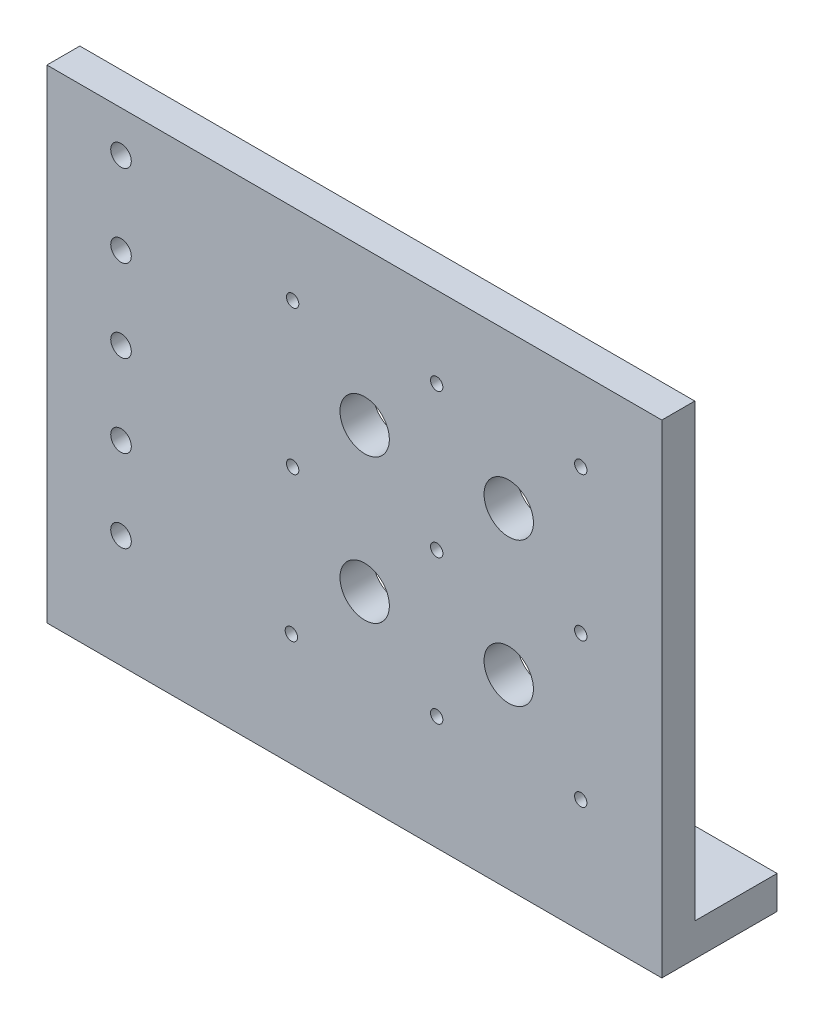
SolidWorks part; units mm, degrees
ref_plane "Front Plane" through (0, 0, 0) normal (0, 0, 1) x (1, 0, 0)
ref_plane "Top Plane" through (0, 0, 0) normal (0, 1, 0) x (1, 0, 0)
ref_plane "Right Plane" through (0, 0, 0) normal (1, 0, 0) x (0, 0, -1)
sketch "Sketch1" plane through (0, 0, 0) normal (0, 0, 1) x (1, 0, 0)
  line L0 (-72.2, 72.2) -> (37.2, 72.2)
  line L5 (-57.2, 57.2) -> (22.2, 57.2)
  line L6 (-57.2, 57.2) -> (-57.2, -22.2)
  line L7 (-57.2, -22.2) -> (22.2, -22.2)
  line L8 (22.2, 57.2) -> (22.2, -22.2)
  line L9 (37.2, 72.2) -> (37.2, -37.2)
  line L10 (-72.2, -37.2) -> (37.2, -37.2)
  line L11 (-72.2, 72.2) -> (-72.2, -37.2)
  circle A0 centre (-52.5, 52.5) radius 1.5
  circle A1 centre (-17.5, 52.5) radius 1.5
  circle A2 centre (17.5, 52.5) radius 1.5
  circle A3 centre (-52.5, 17.5) radius 1.5
  circle A4 centre (-17.5, 17.5) radius 1.5
  circle A5 centre (17.5, 17.5) radius 1.5
  circle A6 centre (17.5, -17.5) radius 1.5
  circle A7 centre (-17.5, -17.5) radius 1.5
  circle A8 centre (-52.8099, -17.8099) radius 1.5
  circle A9 centre (-35, 35) radius 6
  circle A10 centre (0, 35) radius 6
  circle A11 centre (0, 0) radius 6
  circle A12 centre (-35, 0) radius 6
  point P49 (-17.5, 17.5)
  dimension "D1" = 15
  dimension "D2" = 4
extrude "Boss-Extrude1" add sketch "Sketch1" along normal blind 8 contours L8 L5 L6 L7 A12 A11 A10 A9 A8 A7 A6 A5 A4 A3 A2 A1 A0 | L0 L11 L10 L9 L5 L8 L7 L6
sketch "Sketch2" plane through (0, 72.2, 0) normal (0, 1, 0) x (1, 0, 0)
  line L1 (-72.2, -8) -> (-112.2, -8)
  line L2 (-72.2, -8) -> (-72.2, 0)
  line L3 (-72.2, 0) -> (-112.2, 0)
  line L4 (-112.2, -8) -> (-112.2, 0)
  dimension "D1" = 40
extrude "Boss-Extrude2" add sketch "Sketch2" against normal up to surface (109.4 mm away) contours L2 L1 L4 L3 up to face at (-17.5, -37.2, 4)
sketch "Sketch4" plane through (0, 0, 0) normal (0, 0, -1) x (-1, 0, 0)
  line L0 (112.2, 72.2) -> (-37.2, 72.2) construction
  line L1 (112.2, -37.2) -> (112.2, 72.2) construction
  circle A0 centre (94.2, 62.2) radius 2.5
  circle A1 centre (94.2, 42.2) radius 2.5
  circle A2 centre (94.2, 22.2) radius 2.5
  circle A3 centre (94.2, 2.2) radius 2.5
  circle A4 centre (94.2, -17.8) radius 2.5
  dimension "D1" = 5
  dimension "D2" = 10
  dimension "D3" = 18
  dimension "D4" = 5
extrude "Cut-Extrude1" cut sketch "Sketch4" against normal blind 25
sketch "Sketch5" plane through (0, -37.2, 0) normal (0, -1, 0) x (1, 0, 0)
  line L1 (-112.2, 0) -> (37.2, 0)
  line L2 (-112.2, 0) -> (-112.2, -20)
  line L3 (-112.2, -20) -> (37.2, -20)
  line L4 (37.2, 0) -> (37.2, -20)
  line L5 (37.2, 8) -> (-112.2, 8)
  line L6 (37.2, 8) -> (37.2, 0)
  line L7 (37.2, 0) -> (-112.2, 0)
  line L8 (-112.2, 8) -> (-112.2, 0)
  line M2 (-112.2, 0) -> (37.2, 0)
  line M3 (37.2, 0) -> (37.2, 8)
  line M4 (37.2, 8) -> (-112.2, 8)
  line M5 (-112.2, 8) -> (-112.2, 0)
  dimension "D1" = 20
extrude "Boss-Extrude3" add sketch "Sketch5" along normal blind 8 contours M5 M2 M3 M4 | L4 L2 L3 M2
sketch "Sketch6" plane through (0, -37.2, 0) normal (0, 1, 0) x (1, 0, 0)
  line L0 (-112.2, 0) -> (-77.559, 20)
  line L1 (-112.2, 20) -> (37.2, 20) construction
  line L2 (-112.2, 0) -> (37.2, 0) construction
  line L3 (-112.2, 0) -> (-112.2, 20)
  line L4 (-112.2, 20) -> (-77.559, 20)
  dimension "D1" = 30
extrude "Cut-Extrude2" cut sketch "Sketch6" against normal blind 37
sketch "Sketch7" plane through (0, -37.2, 0) normal (0, 1, 0) x (1, 0, 0)
  line L0 (37.2, 20) -> (37.2, 0) construction
  line L1 (-77.559, 20) -> (37.2, 20) construction
  circle A0 centre (22.2, 10) radius 2.5
  circle A1 centre (2.2, 10) radius 2.5
  circle A2 centre (-17.8, 10) radius 2.5
  circle A3 centre (-37.8, 10) radius 2.5
  circle A4 centre (-57.8, 10) radius 2.5
  circle A5 centre (-77.8, 10) radius 2.5
  dimension "D1" = 5
  dimension "D2" = 15
  dimension "D3" = 10
  dimension "D4" = 6
extrude "Cut-Extrude3" cut sketch "Sketch7" against normal blind 10
